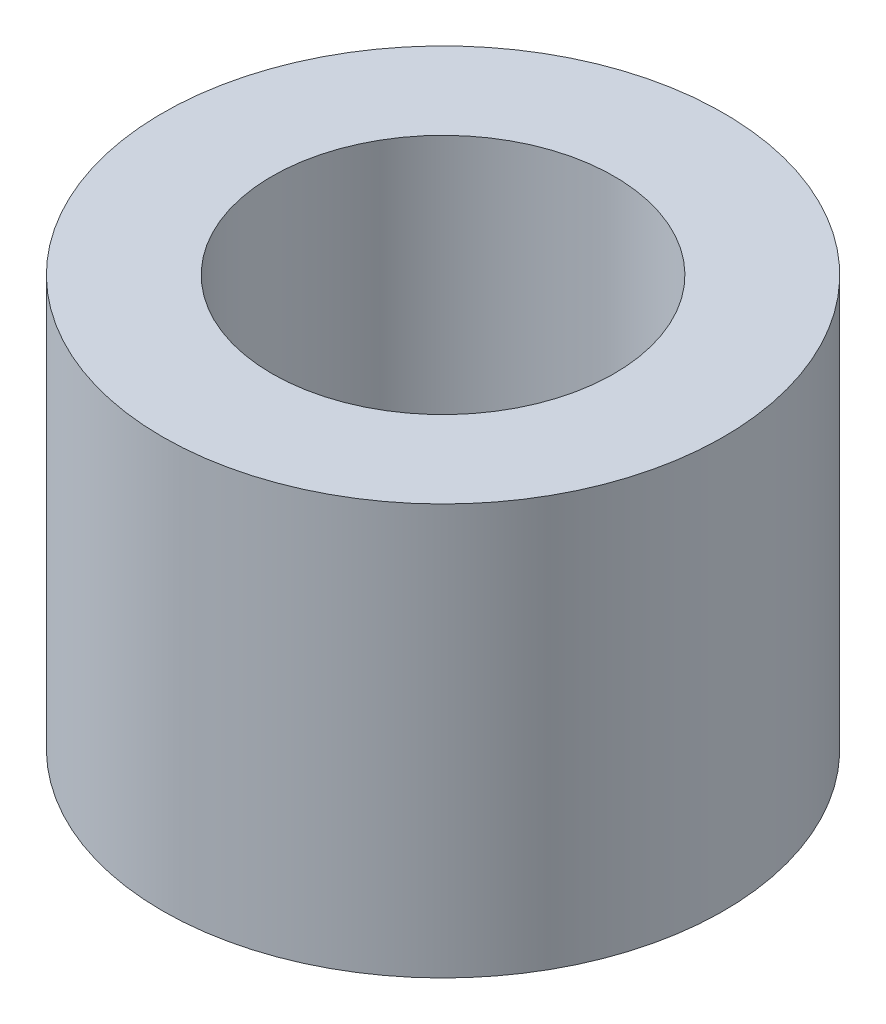
SolidWorks part; units mm, degrees
ref_plane "Front Plane" through (0, 0, 0) normal (0, 0, 1) x (1, 0, 0)
ref_plane "Top Plane" through (0, 0, 0) normal (0, 1, 0) x (1, 0, 0)
ref_plane "Right Plane" through (0, 0, 0) normal (1, 0, 0) x (0, 0, -1)
sketch "Sketch1" plane through (0, 0, 0) normal (0, 1, 0) x (1, 0, 0)
  circle A0 centre (0, 0) radius 15.621
  circle A1 centre (0, 0) radius 9.525
  dimension "D1" = 19.05
  dimension "D2" = 6.096
extrude "Boss-Extrude1" add sketch "Sketch1" along normal blind 22.86
